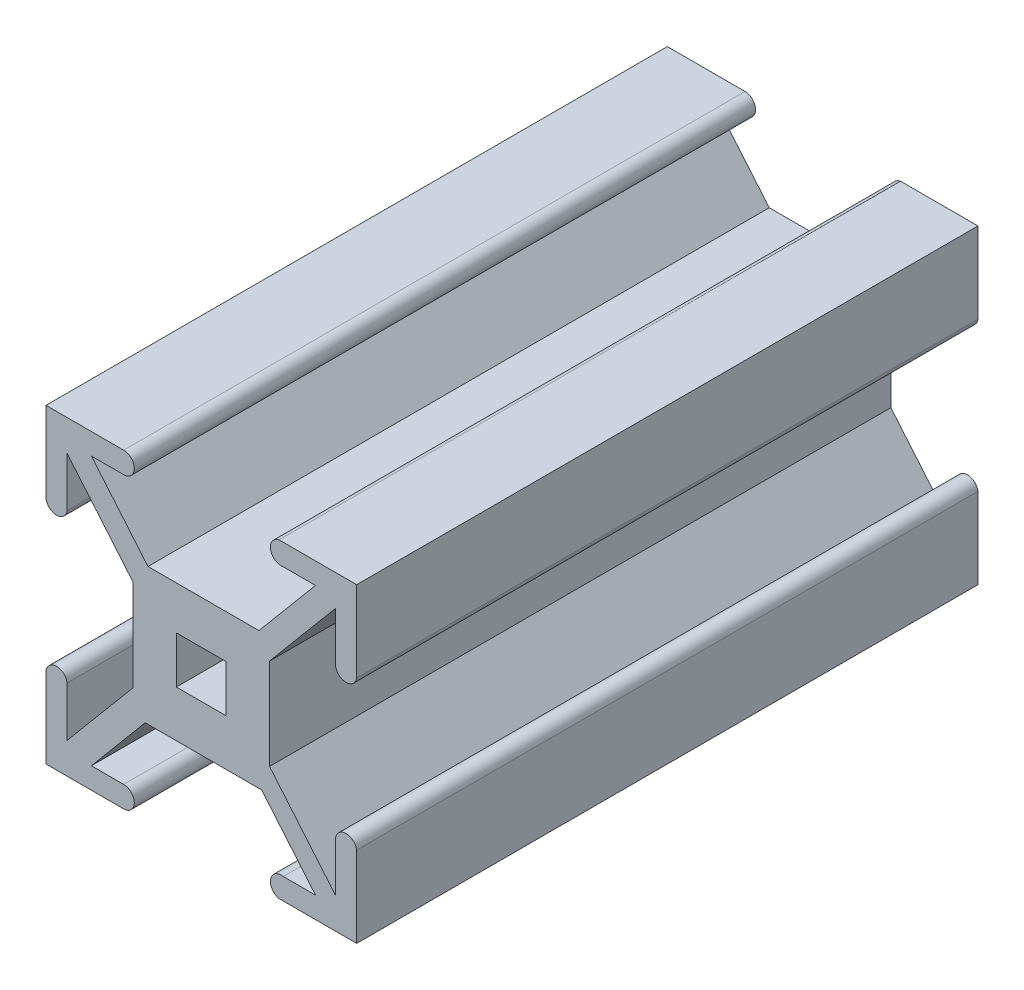
SolidWorks part; units mm, degrees
ref_plane "Front Plane" through (0, 0, 0) normal (0, 0, 1) x (1, 0, 0)
ref_plane "Top Plane" through (0, 0, 0) normal (0, 1, 0) x (1, 0, 0)
ref_plane "Right Plane" through (0, 0, 0) normal (1, 0, 0) x (0, 0, -1)
sketch "Sketch1" plane through (0, 0, 0) normal (0, 0, 1) x (1, 0, 0)
  line L1 (-21.0591, 25) -> (28.9409, 25)
  line L2 (-21.0591, 25) -> (-21.0591, -25)
  line L3 (-21.0591, -25) -> (28.9409, -25)
  line L4 (28.9409, 25) -> (28.9409, -25)
  dimension "D1" = 50
  dimension "D2" = 50
extrude "Boss-Extrude1" add sketch "Sketch1" along normal blind 100
sketch "Sketch2" plane through (0, 0, 0) normal (0, 0, -1) x (-1, 0, 0)
  line L1 (-12.9409, 9) -> (5.0591, 9)
  line L2 (-12.9409, 9) -> (-12.9409, -9)
  line L3 (-12.9409, -9) -> (5.0591, -9)
  line L4 (5.0591, 9) -> (5.0591, -9)
  line L8 (-28.9409, -25) -> (-28.9409, 25) construction
  line L9 (21.0591, 25) -> (21.0591, -25) construction
  line L10 (21.0591, -25) -> (-28.9409, -25) construction
  line L11 (-28.9409, 25) -> (21.0591, 25) construction
  dimension "D1" = 16
  dimension "D2" = 16
  dimension "D3" = 16
  dimension "D4" = 16
extrude "Cut-Extrude2" cut sketch "Sketch2" against normal blind 287
sketch "Sketch3" plane through (0, 0, 0) normal (0, 0, -1) x (-1, 0, 0)
  line L1 (-22.3163, 21.5842) -> (-17.1163, 21.5842)
  line L9 (-28.9409, 25) -> (-16.4651, 25)
  line L10 (-28.9409, 25) -> (21.0591, 25) construction
  line L11 (-17.2817, 15.5842) -> (-22.3163, 21.5842)
  line L12 (-28.9409, 25) -> (-28.9409, 12.5)
  line L13 (-28.9409, -25) -> (-28.9409, 25) construction
  line L15 (8.7183, 15.5842) -> (13.7529, 21.5842)
  line L16 (13.7529, 21.5842) -> (8.5591, 21.5842)
  line L17 (-25.5409, 20.0034) -> (-18.5395, 11.6595)
  line L18 (8.5591, 25) -> (21.0591, 25)
  line L19 (-25.5409, 20.0034) -> (-25.5409, 12.0034)
  line L20 (10.6577, 11.6595) -> (7.0357, 7.3429)
  line L21 (17.6591, 20.0034) -> (10.6577, 11.6595)
  line L22 (17.6591, 20.0034) -> (17.6591, 12.0034)
  line L23 (21.0591, 25) -> (21.0591, 12.5)
  line L24 (-18.5395, 11.6595) -> (-14.9175, 7.3429)
  line L26 (-25.5409, -20.0034) -> (-18.5395, -11.6595)
  line L27 (-25.5409, -20.0034) -> (-25.5409, -12.0034)
  line L28 (-28.9409, -25) -> (-28.9409, -12.5)
  line L29 (-28.9409, -25) -> (-16.4651, -25)
  line L30 (-22.3163, -21.5842) -> (-17.1163, -21.5842)
  line L31 (-17.2817, -15.5842) -> (-22.3163, -21.5842)
  line L32 (17.6591, -20.0034) -> (10.6577, -11.6595)
  line L33 (17.6591, -20.0034) -> (17.6591, -12.0034)
  line L34 (21.0591, -25) -> (21.0591, -12.5)
  line L35 (8.5591, -25) -> (21.0591, -25)
  line L36 (13.7529, -21.5842) -> (8.5591, -21.5842)
  line L37 (8.7183, -15.5842) -> (13.7529, -21.5842)
  line L40 (-13.217, 10.7401) -> (4.6536, 10.7401)
  line L41 (-14.9175, 7.3429) -> (-14.9175, -7.3429)
  line L42 (-13.6531, -11.2599) -> (5.0898, -11.2599)
  line L43 (7.0357, 7.3429) -> (7.0357, -7.3429)
  line L44 (-14.9175, 10.7401) -> (7.0357, -11.2599) construction
  line L45 (-14.9175, -11.2599) -> (7.0357, 10.7401) construction
  line L46 (-17.2817, 15.5842) -> (-13.217, 10.7401)
  line L47 (8.7183, 15.5842) -> (4.6536, 10.7401)
  line L48 (8.7183, -15.5842) -> (5.0898, -11.2599)
  line L49 (-18.5395, -11.6595) -> (-14.9175, -7.3429)
  line L50 (-17.2817, -15.5842) -> (-13.6531, -11.2599)
  line L51 (10.6577, -11.6595) -> (7.0357, -7.3429)
  arc A0 (8.5591, 21.5842) -> (8.5591, 25) centre (8.5591, 23.2921) cw
  arc A1 (-16.4651, 25) -> (-17.1163, 21.5842) centre (-16.7907, 23.2921) cw
  arc A2 (-25.5409, 12.0034) -> (-28.9409, 12.5) centre (-27.2409, 12.2517) cw
  arc A3 (17.6591, 12.0034) -> (21.0591, 12.5) centre (19.3591, 12.2517) ccw
  arc A4 (-25.5409, -12.0034) -> (-28.9409, -12.5) centre (-27.2409, -12.2517) ccw
  arc A5 (-16.4651, -25) -> (-17.1163, -21.5842) centre (-16.7907, -23.2921) ccw
  arc A6 (17.6591, -12.0034) -> (21.0591, -12.5) centre (19.3591, -12.2517) cw
  arc A7 (8.5591, -21.5842) -> (8.5591, -25) centre (8.5591, -23.2921) ccw
  point P23 (-3.9409, -0.2599)
extrude "Cut-Extrude5" cut sketch "Sketch3" against normal blind 287 flip side to cut
sketch "Sketch4" plane through (0, 0, 0) normal (0, 0, -1) x (-1, 0, 0)
  line L1 (-12.9409, 9) -> (5.0591, 9)
  line L2 (-12.9409, 9) -> (-12.9409, -9)
  line L3 (-12.9409, -9) -> (5.0591, -9)
  line L4 (5.0591, 9) -> (5.0591, -9)
extrude "Boss-Extrude2" add sketch "Sketch4" against normal blind 100
sketch "Sketch5" plane through (0, 0, 0) normal (0, 0, -1) x (-1, 0, 0)
  line L1 (-7.9175, 3.7766) -> (0.0825, 3.7766)
  line L2 (-7.9175, 3.7766) -> (-7.9175, -3.7766)
  line L3 (-7.9175, -3.7766) -> (0.0825, -3.7766)
  line L4 (0.0825, 3.7766) -> (0.0825, -3.7766)
  line L5 (-7.9175, 3.7766) -> (0.0825, -3.7766) construction
  line L6 (-7.9175, -3.7766) -> (0.0825, 3.7766) construction
  point P0 (-3.9175, 0)
extrude "Cut-Extrude6" cut sketch "Sketch5" against normal blind 250
